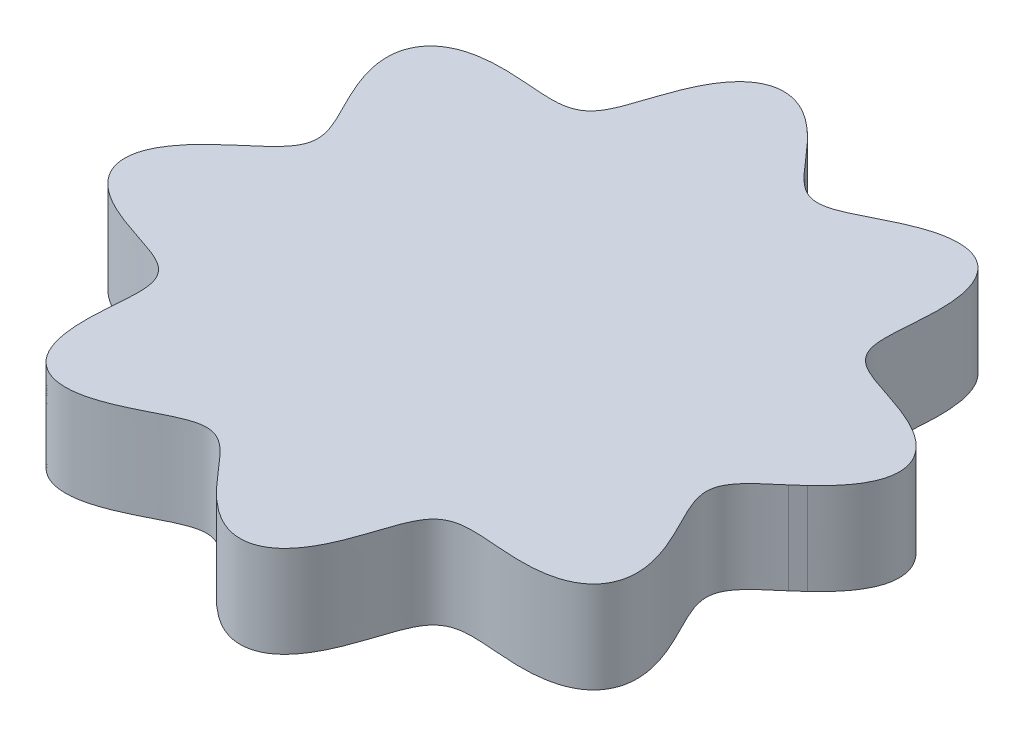
SolidWorks part; units mm, degrees
ref_plane "Ebene vorne" through (0, 0, 0) normal (0, 0, 1) x (1, 0, 0)
ref_plane "Ebene oben" through (0, 0, 0) normal (0, 1, 0) x (1, 0, 0)
ref_plane "Ebene rechts" through (0, 0, 0) normal (1, 0, 0) x (0, 0, -1)
sketch "Skizze2" plane through (0, 0, 0) normal (0, 1, 0) x (1, 0, 0)
  spline S0 degree 4 poles (6.7775, -4.8918) (6.8359, -4.8447) (6.9432, -4.7405) (7.0982, -4.5135) (7.1877, -4.125) (7.1516, -3.7058) (7.0302, -3.2797) (6.8684, -2.8888) (6.6913, -2.5269) (6.5301, -2.2152) (6.4009, -1.9455) (6.3135, -1.7142) (6.2655, -1.5248) (6.2543, -1.3239) (6.3007, -1.1235) (6.4035, -0.9402) (6.5361, -0.7781) (6.689, -0.6257) (6.8394, -0.4904) (7.0117, -0.3412) (7.1488, -0.2254) (7.3587, -0.0389) (7.457, 0.0518) (7.6775, 0.2678) (7.803, 0.4145) (7.9667, 0.62) (8.0837, 0.8131) (8.1893, 1.0337) (8.2511, 1.2619) (8.2715, 1.5451) (8.1941, 1.8656) (7.981, 2.1819) (7.6509, 2.4519) (7.2727, 2.661) (6.8671, 2.8268) (6.4919, 2.9527) (6.1559, 3.0605) (5.8628, 3.1658) (5.619, 3.278) (5.3953, 3.4327) (5.24, 3.6609) (5.1799, 3.9264) (5.1683, 4.1942) (5.1825, 4.5052) (5.2112, 4.8564) (5.2392, 5.251) (5.2419, 5.6885) (5.1957, 6.1182) (5.0746, 6.5261) (4.8439, 6.886) (4.4851, 7.12) (4.0599, 7.1867) (3.6323, 7.1348) (3.2167, 7.0075) (2.8151, 6.835) (2.4633, 6.658) (2.1526, 6.4987) (1.8741, 6.3705) (1.6269, 6.2833) (1.3663, 6.2436) (1.1083, 6.2999) (0.8902, 6.4375) (0.7028, 6.6068) (0.4992, 6.8268) (0.2749, 7.0905) (0.054, 7.3469) (-0.1741, 7.5862) (-0.4171, 7.8098) (-0.673, 8.0085) (-0.9976, 8.1914) (-1.4117, 8.2929) (-1.8291, 8.2198) (-2.1815, 7.9806) (-2.4519, 7.6515) (-2.6608, 7.2727) (-2.8268, 6.8675) (-2.9526, 6.492) (-3.0604, 6.1561) (-3.1657, 5.863) (-3.2779, 5.6192) (-3.4326, 5.3954) (-3.6607, 5.2401) (-3.9262, 5.1799) (-4.194, 5.1683) (-4.5049, 5.1824) (-4.8561, 5.2112) (-5.2508, 5.2392) (-5.6883, 5.2419) (-6.118, 5.1958) (-6.5259, 5.0747) (-6.8858, 4.8441) (-7.1199, 4.4853) (-7.1867, 4.0602) (-7.1348, 3.6325) (-7.0076, 3.2169) (-6.8351, 2.8153) (-6.6581, 2.4635) (-6.4988, 2.1528) (-6.3706, 1.8743) (-6.2834, 1.6271) (-6.2436, 1.3665) (-6.2998, 1.1085) (-6.4373, 0.8904) (-6.6066, 0.703) (-6.8267, 0.4993) (-7.0903, 0.2751) (-7.3886, 0.0181) (-7.7042, -0.289) (-7.981, -0.6244) (-8.1913, -0.9974) (-8.2928, -1.4114) (-8.2199, -1.8289) (-7.9808, -2.1813) (-7.6517, -2.4518) (-7.2729, -2.6607) (-6.8677, -2.8267) (-6.4922, -2.9525) (-6.1563, -3.0603) (-5.8632, -3.1656) (-5.6194, -3.2778) (-5.3956, -3.4324) (-5.2402, -3.6605) (-5.1799, -3.926) (-5.1683, -4.1938) (-5.1824, -4.5047) (-5.2112, -4.8559) (-5.2391, -5.2506) (-5.2419, -5.688) (-5.1958, -6.1177) (-5.0748, -6.5257) (-4.8443, -6.8856) (-4.4856, -7.1198) (-4.0605, -7.1867) (-3.6328, -7.1349) (-3.2172, -7.0077) (-2.8155, -6.8353) (-2.4053, -6.6287) (-2.0363, -6.4391) (-1.6929, -6.2935) (-1.3668, -6.2436) (-1.1087, -6.2997) (-0.8906, -6.4372) (-0.7031, -6.6064) (-0.4995, -6.8265) (-0.2752, -7.0901) (-0.0183, -7.3884) (0.2889, -7.704) (0.6242, -7.9809) (0.9972, -8.1912) (1.4112, -8.2928) (1.8286, -8.22) (2.1811, -7.981) (2.4516, -7.6519) (2.6606, -7.2731) (2.8267, -6.8679) (2.9525, -6.4924) (3.0603, -6.1566) (3.1656, -5.8634) (3.2777, -5.6196) (3.4323, -5.3957) (3.6603, -5.2403) (3.9258, -5.18) (4.1936, -5.1683) (4.5045, -5.1824) (4.8557, -5.2112) (5.2503, -5.2391) (5.6878, -5.2419) (6.1175, -5.1959) (6.5254, -5.0749) (6.8854, -4.8444) (7.1197, -4.4858) (7.1867, -4.0607) (7.1349, -3.633) (7.0078, -3.2174) (6.8353, -2.8157) (6.6584, -2.464) (6.5139, -2.1822) (6.412, -1.9643) (6.3504, -1.8124) (6.3081, -1.6882) (6.2763, -1.5608) (6.2597, -1.4303) (6.2641, -1.289) (6.2993, -1.1419) (6.3601, -1.0163) (6.4314, -0.9106) (6.4963, -0.8291) (6.5521, -0.766) (6.6701, -0.6454) (6.771, -0.5485) (7.0483, -0.3099) (7.1636, -0.212) (7.3634, -0.0351) (7.497, 0.0898) (7.6295, 0.2219) (7.7579, 0.3608) (7.8773, 0.5051) (7.988, 0.6577) (8.0849, 0.8174) (8.1657, 0.9852) (8.2397, 1.204) (8.2783, 1.4799) (8.2212, 1.806) (8.0224, 2.1277) (7.7445, 2.382) (7.4242, 2.5822) (7.0809, 2.7424) (6.7407, 2.8698) (6.4106, 2.9786) (6.0947, 3.0812) (5.8345, 3.1769) (5.6198, 3.2806) (5.4899, 3.3723) (5.4312, 3.4256) (5.4034, 3.454) knots 0 0 0 0 0 0.004325 0.008649 0.015609 0.022568 0.028398 0.034229 0.040059 0.04589 0.04871 0.051531 0.054351 0.057172 0.060227 0.063283 0.066339 0.069394 0.07245 0.075506 0.078562 0.081617 0.085059 0.0885 0.091941 0.095383 0.098824 0.102265 0.105707 0.109148 0.11506 0.120972 0.127309 0.133645 0.139981 0.146317 0.150202 0.154087 0.157973 0.161858 0.16574 0.169621 0.173503 0.177385 0.183716 0.190046 0.196377 0.202707 0.208614 0.214522 0.220593 0.226665 0.23299 0.239315 0.24564 0.251965 0.255759 0.259553 0.263347 0.267141 0.270794 0.274447 0.2781 0.281752 0.288125 0.294497 0.297683 0.30087 0.307242 0.313188 0.319135 0.325047 0.330959 0.337296 0.343632 0.349968 0.356304 0.36019 0.364075 0.36796 0.371845 0.375727 0.379609 0.383491 0.387372 0.393703 0.400033 0.406364 0.412694 0.418601 0.424508 0.43058 0.436652 0.442977 0.449302 0.455627 0.461952 0.465746 0.469541 0.473335 0.477129 0.480782 0.484434 0.488087 0.49174 0.498112 0.504484 0.510857 0.517229 0.523175 0.529121 0.535034 0.540946 0.547283 0.553619 0.559955 0.566292 0.570177 0.574062 0.577948 0.581833 0.585715 0.589596 0.593478 0.59736 0.60369 0.610021 0.616351 0.622681 0.628588 0.634495 0.640567 0.646639 0.652964 0.659289 0.665614 0.671939 0.679528 0.683322 0.687117 0.690769 0.694422 0.698075 0.701727 0.708099 0.714472 0.720844 0.727216 0.733162 0.739108 0.745021 0.750933 0.75727 0.763606 0.769943 0.776279 0.780164 0.78405 0.787935 0.791821 0.795702 0.799584 0.803466 0.807347 0.813678 0.820008 0.826338 0.832668 0.838575 0.844482 0.850554 0.856626 0.862951 0.869276 0.875602 0.881927 0.885721 0.887618 0.889516 0.891413 0.89331 0.895207 0.897104 0.899553 0.902001 0.903225 0.90445 0.905674 0.906898 0.911795 0.916692 0.919411 0.922131 0.92485 0.927569 0.930289 0.933008 0.935728 0.938447 0.941102 0.943757 0.949068 0.954414 0.959761 0.965237 0.970713 0.97619 0.981666 0.986249 0.990833 0.995416 0.997708 1 1 1 1 1 construction
  spline S1 degree 4 poles (7.4, 0) (7.4364, 0.0337) (7.5074, 0.1012) (7.6775, 0.2678) (7.803, 0.4145) (7.9667, 0.62) (8.0837, 0.8131) (8.1893, 1.0337) (8.2511, 1.2619) (8.2715, 1.5451) (8.1941, 1.8656) (7.981, 2.1819) (7.6509, 2.4519) (7.2727, 2.661) (6.8671, 2.8268) (6.4919, 2.9527) (6.1559, 3.0605) (5.8628, 3.1658) (5.619, 3.278) (5.3953, 3.4327) (5.24, 3.6609) (5.1799, 3.9264) (5.1683, 4.1942) (5.1825, 4.5052) (5.2112, 4.8564) (5.2392, 5.251) (5.2419, 5.6885) (5.1957, 6.1182) (5.0746, 6.5261) (4.8439, 6.886) (4.4851, 7.12) (4.0599, 7.1867) (3.6323, 7.1348) (3.2167, 7.0075) (2.8151, 6.835) (2.4633, 6.658) (2.1526, 6.4987) (1.8741, 6.3705) (1.6269, 6.2833) (1.3663, 6.2436) (1.1083, 6.2999) (0.8902, 6.4375) (0.7028, 6.6068) (0.4992, 6.8268) (0.2749, 7.0905) (0.054, 7.3469) (-0.1741, 7.5862) (-0.4171, 7.8098) (-0.673, 8.0085) (-0.9976, 8.1914) (-1.4117, 8.2929) (-1.8291, 8.2198) (-2.1815, 7.9806) (-2.4519, 7.6515) (-2.6608, 7.2727) (-2.8268, 6.8675) (-2.9526, 6.492) (-3.0604, 6.1561) (-3.1657, 5.863) (-3.2779, 5.6192) (-3.4326, 5.3954) (-3.6607, 5.2401) (-3.9262, 5.1799) (-4.194, 5.1683) (-4.5049, 5.1824) (-4.8561, 5.2112) (-5.2508, 5.2392) (-5.6883, 5.2419) (-6.118, 5.1958) (-6.5259, 5.0747) (-6.8858, 4.8441) (-7.1199, 4.4853) (-7.1867, 4.0602) (-7.1348, 3.6325) (-7.0076, 3.2169) (-6.8351, 2.8153) (-6.6581, 2.4635) (-6.4988, 2.1528) (-6.3706, 1.8743) (-6.2834, 1.6271) (-6.2436, 1.3665) (-6.2998, 1.1085) (-6.4373, 0.8904) (-6.6066, 0.703) (-6.8267, 0.4993) (-7.0903, 0.2751) (-7.3886, 0.0181) (-7.7042, -0.289) (-7.981, -0.6244) (-8.1913, -0.9974) (-8.2928, -1.4114) (-8.2199, -1.8289) (-7.9808, -2.1813) (-7.6517, -2.4518) (-7.2729, -2.6607) (-6.8677, -2.8267) (-6.4922, -2.9525) (-6.1563, -3.0603) (-5.8632, -3.1656) (-5.6194, -3.2778) (-5.3956, -3.4324) (-5.2402, -3.6605) (-5.1799, -3.926) (-5.1683, -4.1938) (-5.1824, -4.5047) (-5.2112, -4.8559) (-5.2391, -5.2506) (-5.2419, -5.688) (-5.1958, -6.1177) (-5.0748, -6.5257) (-4.8443, -6.8856) (-4.4856, -7.1198) (-4.0605, -7.1867) (-3.6328, -7.1349) (-3.2172, -7.0077) (-2.8155, -6.8353) (-2.4053, -6.6287) (-2.0363, -6.4391) (-1.6929, -6.2935) (-1.3668, -6.2436) (-1.1087, -6.2997) (-0.8906, -6.4372) (-0.7031, -6.6064) (-0.4995, -6.8265) (-0.2752, -7.0901) (-0.0183, -7.3884) (0.2889, -7.704) (0.6242, -7.9809) (0.9972, -8.1912) (1.4112, -8.2928) (1.8286, -8.22) (2.1811, -7.981) (2.4516, -7.6519) (2.6606, -7.2731) (2.8267, -6.8679) (2.9525, -6.4924) (3.0603, -6.1566) (3.1656, -5.8634) (3.2777, -5.6196) (3.4323, -5.3957) (3.6603, -5.2403) (3.9258, -5.18) (4.1936, -5.1683) (4.5045, -5.1824) (4.8557, -5.2112) (5.2503, -5.2391) (5.6878, -5.2419) (6.1175, -5.1959) (6.5254, -5.0749) (6.8854, -4.8444) (7.1197, -4.4858) (7.1867, -4.0607) (7.1349, -3.633) (7.0078, -3.2174) (6.8353, -2.8157) (6.6584, -2.464) (6.5139, -2.1822) (6.412, -1.9643) (6.3504, -1.8124) (6.3081, -1.6882) (6.2763, -1.5608) (6.2597, -1.4303) (6.2641, -1.289) (6.2993, -1.1419) (6.3601, -1.0163) (6.4314, -0.9106) (6.4963, -0.8291) (6.5521, -0.766) (6.6701, -0.6454) (6.771, -0.5485) (6.9934, -0.3571) (7.0944, -0.2709) (7.1478, -0.2246) knots 0.081617 0.081617 0.081617 0.081617 0.081617 0.085059 0.0885 0.091941 0.095383 0.098824 0.102265 0.105707 0.109148 0.11506 0.120972 0.127309 0.133645 0.139981 0.146317 0.150202 0.154087 0.157973 0.161858 0.16574 0.169621 0.173503 0.177385 0.183716 0.190046 0.196377 0.202707 0.208614 0.214522 0.220593 0.226665 0.23299 0.239315 0.24564 0.251965 0.255759 0.259553 0.263347 0.267141 0.270794 0.274447 0.2781 0.281752 0.288125 0.294497 0.297683 0.30087 0.307242 0.313188 0.319135 0.325047 0.330959 0.337296 0.343632 0.349968 0.356304 0.36019 0.364075 0.36796 0.371845 0.375727 0.379609 0.383491 0.387372 0.393703 0.400033 0.406364 0.412694 0.418601 0.424508 0.43058 0.436652 0.442977 0.449302 0.455627 0.461952 0.465746 0.469541 0.473335 0.477129 0.480782 0.484434 0.488087 0.49174 0.498112 0.504484 0.510857 0.517229 0.523175 0.529121 0.535034 0.540946 0.547283 0.553619 0.559955 0.566292 0.570177 0.574062 0.577948 0.581833 0.585715 0.589596 0.593478 0.59736 0.60369 0.610021 0.616351 0.622681 0.628588 0.634495 0.640567 0.646639 0.652964 0.659289 0.665614 0.671939 0.679528 0.683322 0.687117 0.690769 0.694422 0.698075 0.701727 0.708099 0.714472 0.720844 0.727216 0.733162 0.739108 0.745021 0.750933 0.75727 0.763606 0.769943 0.776279 0.780164 0.78405 0.787935 0.791821 0.795702 0.799584 0.803466 0.807347 0.813678 0.820008 0.826338 0.832668 0.838575 0.844482 0.850554 0.856626 0.862951 0.869276 0.875602 0.881927 0.885721 0.887618 0.889516 0.891413 0.89331 0.895207 0.897104 0.899553 0.902001 0.903225 0.90445 0.905674 0.906898 0.911795 0.916692 0.916692 0.916692 0.916692 0.916692
  spline S2 degree 1 poles (7.4, 0) (7.1478, -0.2246) knots 0 0 1 1
extrude "Aufsatz-Linear austragen1" add sketch "Skizze2" along normal blind 2.3
